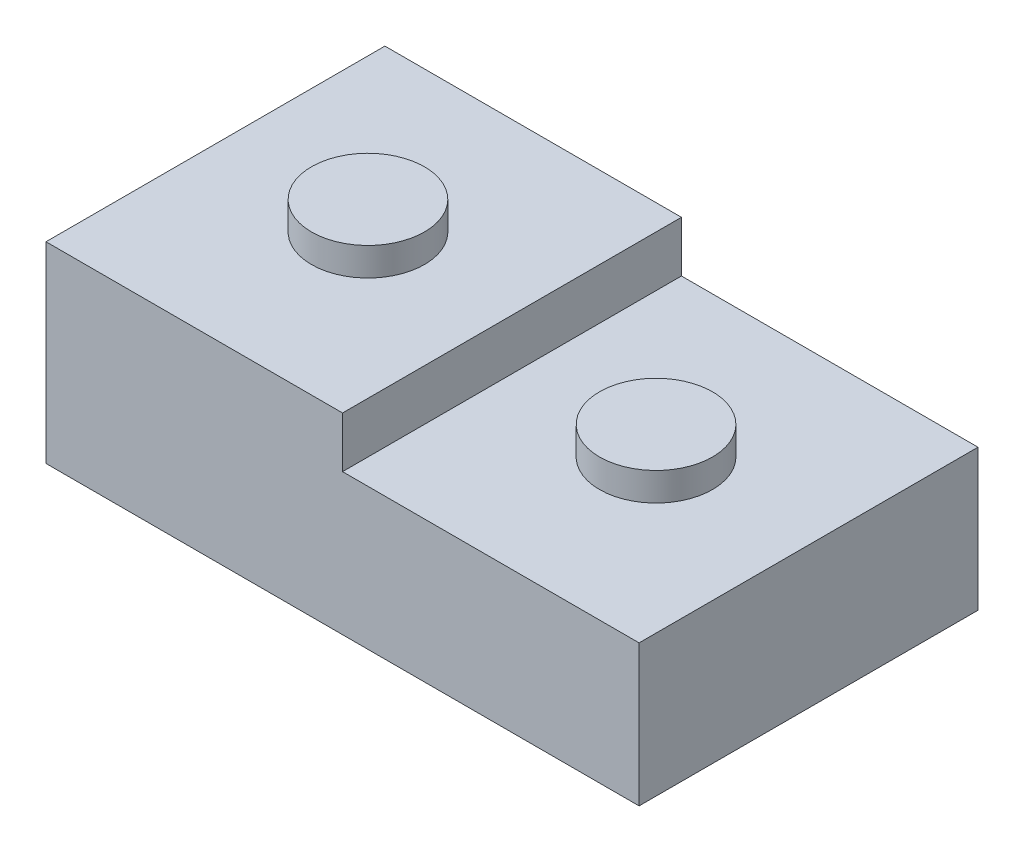
SolidWorks part; units mm, degrees
ref_plane "Front Plane" through (0, 0, 0) normal (0, 0, 1) x (1, 0, 0)
ref_plane "Top Plane" through (0, 0, 0) normal (0, 1, 0) x (1, 0, 0)
ref_plane "Right Plane" through (0, 0, 0) normal (1, 0, 0) x (0, 0, -1)
sketch "Sketch1" plane through (0, 0, 0) normal (0, 1, 0) x (1, 0, 0)
  line L1 (-105, 60) -> (105, 60)
  line L2 (-105, 60) -> (-105, -60)
  line L3 (-105, -60) -> (105, -60)
  line L4 (105, 60) -> (105, -60)
  line L5 (-105, 60) -> (105, -60) construction
  line L6 (-105, -60) -> (105, 60) construction
  point P0 (0, 0)
  dimension "D1" = 120
  dimension "D2" = 210
extrude "Boss-Extrude1" add sketch "Sketch1" along normal blind 50
sketch "Sketch2" plane through (0, 50, 0) normal (0, 1, 0) x (1, 0, 0)
  line L0 (-105, -60) -> (105, -60) construction
  line L1 (-105, 60) -> (0, 60)
  line L2 (-105, 60) -> (-105, -60)
  line L3 (-105, -60) -> (0, -60)
  line L4 (0, 60) -> (0, -60)
extrude "Boss-Extrude2" add sketch "Sketch2" along normal blind 18
sketch "Sketch3" plane through (0, 68, 0) normal (0, 1, 0) x (1, 0, 0)
  line L0 (0, 0) -> (-50000, 0) construction
  line L1 (0, -60) -> (0, 60) construction
  line L2 (-105, 60) -> (-105, -60) construction
  circle A0 centre (-51, 0) radius 20
  point P4 (0, 0)
  dimension "D1" = 20
  dimension "D2" = 54
extrude "Boss-Extrude3" add sketch "Sketch3" along normal blind 10
sketch "Sketch4" plane through (0, 50, 0) normal (0, 1, 0) x (1, 0, 0)
  line L0 (0, 0) -> (50000, 0) construction
  line L1 (105, -60) -> (105, 60) construction
  circle A0 centre (51, 0) radius 20
  dimension "D1" = 20
  dimension "D2" = 54
extrude "Boss-Extrude4" add sketch "Sketch4" along normal blind 10
